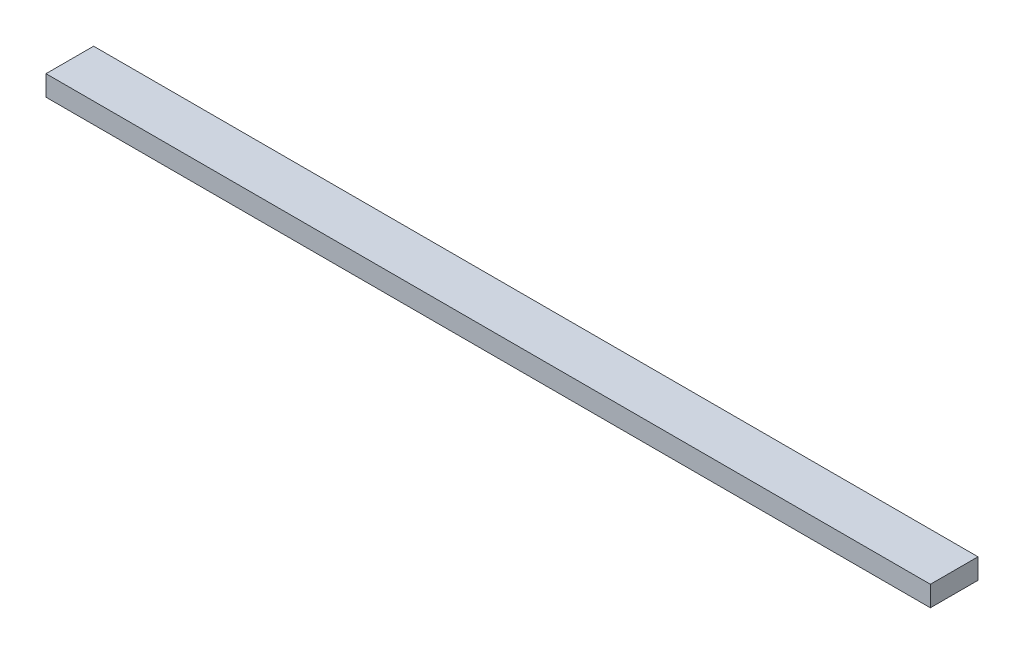
SolidWorks part; units mm, degrees
material "Pine"
ref_plane "Front Plane" through (0, 0, 0) normal (0, 0, 1) x (1, 0, 0)
ref_plane "Top Plane" through (0, 0, 0) normal (0, 1, 0) x (1, 0, 0)
ref_plane "Right Plane" through (0, 0, 0) normal (1, 0, 0) x (0, 0, -1)
sketch "Sketch1" plane through (0, 0, 0) normal (1, 0, 0) x (0, 0, -1)
  line L1 (44.45, -19.05) -> (-44.45, -19.05)
  line L2 (44.45, -19.05) -> (44.45, 19.05)
  line L3 (44.45, 19.05) -> (-44.45, 19.05)
  line L4 (-44.45, -19.05) -> (-44.45, 19.05)
  line L5 (44.45, -19.05) -> (-44.45, 19.05) construction
  line L6 (44.45, 19.05) -> (-44.45, -19.05) construction
  point P0 (0, 0)
  dimension "D1" = 88.9
  dimension "D2" = 38.1
extrude "Boss-Extrude1" add sketch "Sketch1" along normal up to surface (1651 mm away)
